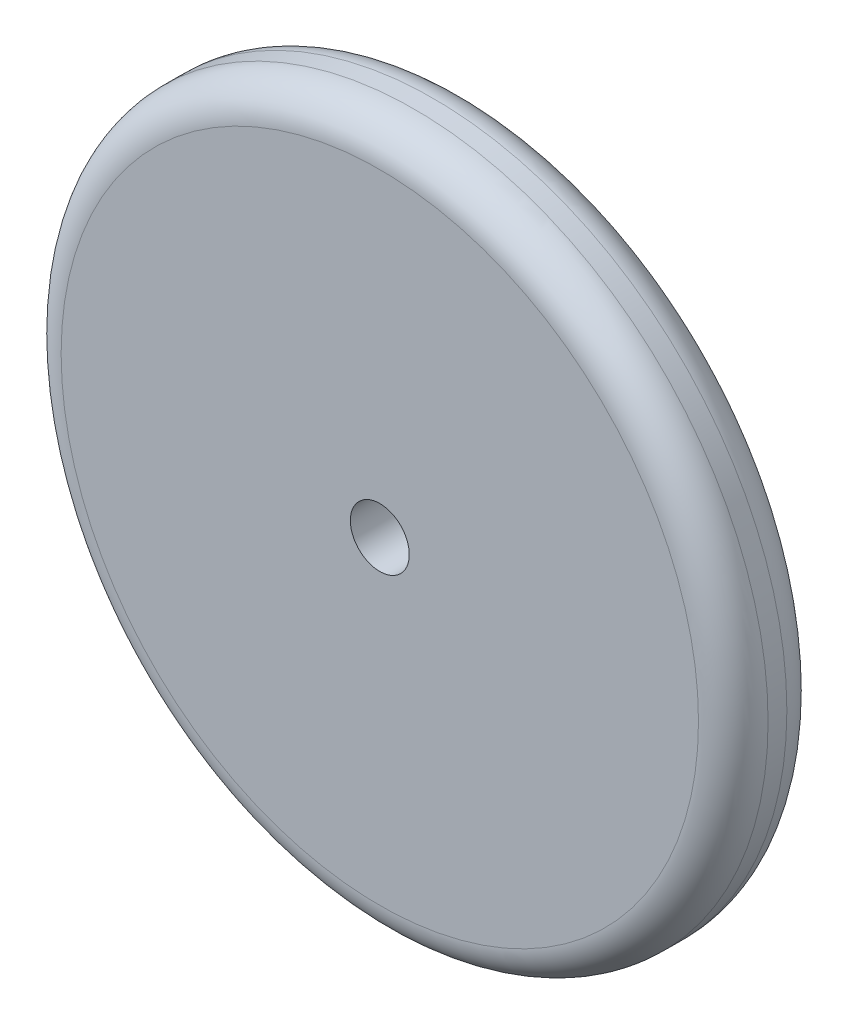
SolidWorks part; units mm, degrees
ref_plane "Front Plane" through (0, 0, 0) normal (0, 0, 1) x (1, 0, 0)
ref_plane "Top Plane" through (0, 0, 0) normal (0, 1, 0) x (1, 0, 0)
ref_plane "Right Plane" through (0, 0, 0) normal (1, 0, 0) x (0, 0, -1)
sketch "Sketch1" plane through (0, 0, 0) normal (0, 0, 1) x (1, 0, 0)
  circle A0 centre (0, 0) radius 152.4
  circle A1 centre (0, 0) radius 12.7
  dimension "D1" = 304.8
  dimension "D2" = 25.4
extrude "Boss-Extrude1" add sketch "Sketch1" along normal blind 38.1
fillet "Fillet1" radius 15 2 edges at (152.4, 0, 0) (152.4, 0, 38.1)
